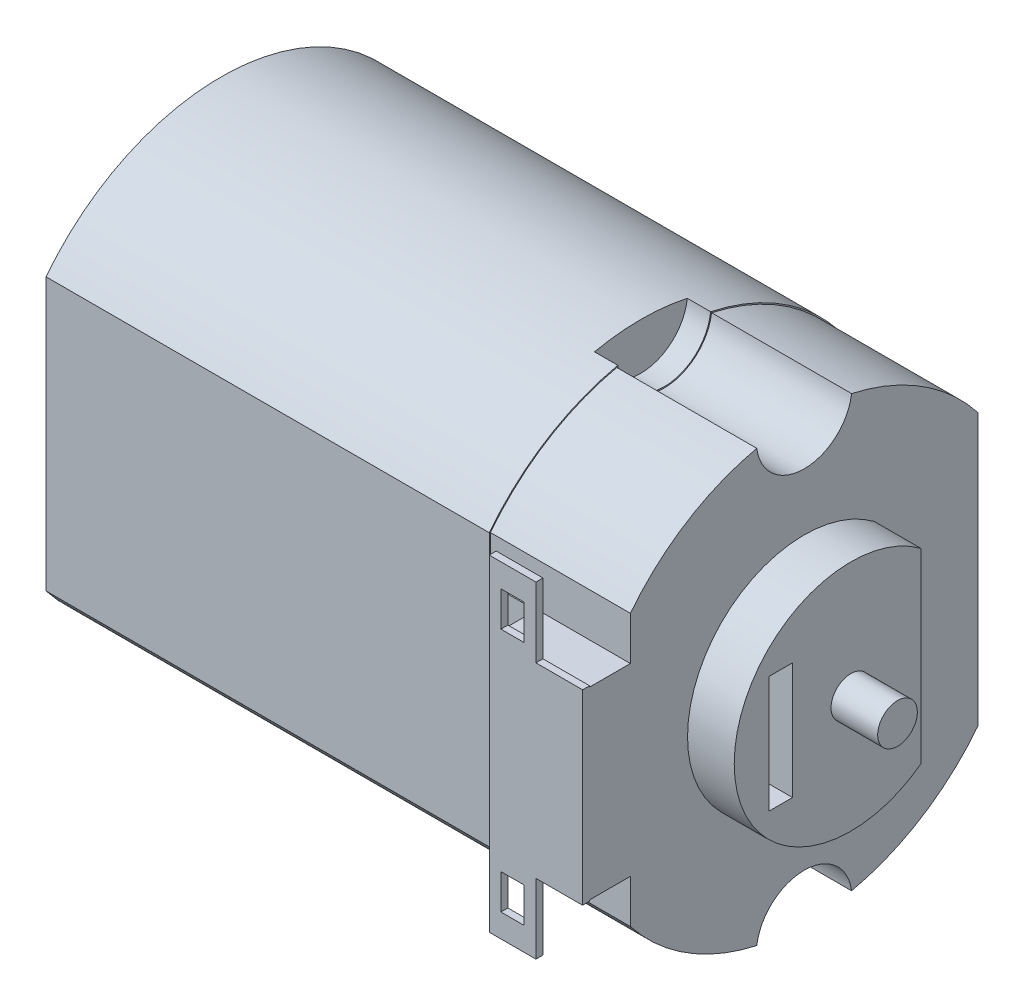
SolidWorks part; units mm, degrees
ref_plane "Front Plane" through (0, 0, 0) normal (0, 0, 1) x (1, 0, 0)
ref_plane "Top Plane" through (0, 0, 0) normal (0, 1, 0) x (1, 0, 0)
ref_plane "Right Plane" through (0, 0, 0) normal (1, 0, 0) x (0, 0, -1)
sketch "Sketch1" plane through (0, 0, 0) normal (1, 0, 0) x (0, 0, -1)
  line L2 (-7.5, 5.831) -> (-7.5, -5.831)
  line L4 (7.5, 5.831) -> (7.5, -5.831)
  line L5 (-7.5, 7.5) -> (7.5, -7.5) construction
  line L6 (-7.5, -7.5) -> (7.5, 7.5) construction
  arc A0 (-7.5, -5.831) -> (7.5, -5.831) centre (0, 0) ccw
  arc A1 (7.5, 5.831) -> (-7.5, 5.831) centre (0, 0) ccw
  dimension "D1" = 19
  dimension "D2" = 15
extrude "Boss-Extrude1" add sketch "Sketch1" along normal blind 25
sketch "Sketch2" plane through (25, 0, 0) normal (1, 0, 0) x (0, 0, -1)
  line L0 (0, -10.4614) -> (0, 9.9981) construction
  line L1 (-8.5237, 0) -> (12.0541, 0) construction
  circle A0 centre (0, 9.5) radius 2
  circle A1 centre (0, -9.5) radius 2
  dimension "D1" = 4
  dimension "D2" = 9.5
extrude "Cut-Extrude1" cut sketch "Sketch2" against normal blind 7
sketch "Sketch3" plane through (25, 0, 0) normal (1, 0, 0) x (0, 0, -1)
  line L0 (3, 4) -> (3, -4)
  line L1 (-8.9719, 0) -> (9.9494, 0) construction
  line L3 (-3.5, 2.5) -> (-2.5, 2.5)
  line L4 (-3.5, 2.5) -> (-3.5, -2.5)
  line L5 (-3.5, -2.5) -> (-2.5, -2.5)
  line L6 (-2.5, 2.5) -> (-2.5, -2.5)
  line L7 (-3.5, 2.5) -> (-2.5, -2.5) construction
  line L8 (-3.5, -2.5) -> (-2.5, 2.5) construction
  arc A0 (3, 4) -> (3, -4) centre (0, 0) ccw
  point P5 (-3, 0)
  dimension "D1" = 10
  dimension "D2" = 3
  dimension "D3" = 5
  dimension "D4" = 1
  dimension "D5" = 2.5
extrude "Boss-Extrude2" add sketch "Sketch3" along normal blind 2
sketch "Sketch4" plane through (27, 0, 0) normal (1, 0, 0) x (0, 0, -1)
  circle A0 centre (0, 0) radius 0.85
  dimension "D1" = 1.7
extrude "Boss-Extrude3" add sketch "Sketch4" along normal blind 2
sketch "Sketch5" plane through (0, 0, 7.5) normal (0, 0, 1) x (1, 0, 0)
  line L0 (25, 5.831) -> (25, -5.831) construction
  line L1 (25, 4) -> (21, 4)
  line L2 (25, 4) -> (25, -4)
  line L3 (25, -4) -> (21, -4)
  line L4 (21, 4) -> (21, -4)
  point P6 (23, 4)
  dimension "D1" = 2
  dimension "D2" = 8
  dimension "D3" = 4
extrude "Boss-Extrude4" add sketch "Sketch5" along normal blind 2
sketch "Sketch6" plane through (0, -4, 0) normal (0, -1, 0) x (1, 0, 0)
  line L1 (21, 9.5) -> (23, 9.5)
  line L2 (21, 9.5) -> (21, 9.2)
  line L3 (21, 9.2) -> (23, 9.2)
  line L4 (23, 9.5) -> (23, 9.2)
  dimension "D1" = 2
  dimension "D2" = 0.3
extrude "Boss-Extrude5" add sketch "Sketch6" along normal blind 3
mirror "Mirror1" about plane through (0, 0, 0) normal (0, 1, 0) of "Boss-Extrude5"
sketch "Sketch7" plane through (0, 0, 9.5) normal (0, 0, 1) x (1, 0, 0)
  line L0 (29.8009, 0) -> (19.4181, 0) construction
  line L1 (22, 7) -> (22, -7) construction
  line L2 (23, 7) -> (21, 7) construction
  line L3 (23, -7) -> (21, -7) construction
  line L4 (21.5, -6) -> (22.5, -6)
  line L5 (21.5, 6) -> (22.5, 6)
  line L6 (21.5, 6) -> (21.5, 4.5)
  line L7 (21.5, 4.5) -> (22.5, 4.5)
  line L8 (22.5, 6) -> (22.5, 4.5)
  line L9 (21.5, 6) -> (22.5, 4.5) construction
  line L10 (21.5, 4.5) -> (22.5, 6) construction
  line L11 (21.5, -6) -> (21.5, -4.5)
  line L12 (21.5, -4.5) -> (22.5, -4.5)
  line L13 (22.5, -6) -> (22.5, -4.5)
  point P9 (22, 5.25)
  dimension "D1" = 1
  dimension "D2" = 1.5
  dimension "D3" = 1
extrude "Cut-Extrude2" cut sketch "Sketch7" against normal blind 1
sketch "Sketch8" plane through (25, 0, 0) normal (1, 0, 0) x (0, 0, -1)
  line L0 (-7.45, 5.8138) -> (-7.45, 3.95)
  line L1 (-7.45, 3.95) -> (-9.2, 3.95)
  line L3 (-9.2, -3.95) -> (-7.45, -3.95)
  line L4 (-7.45, -3.95) -> (-7.45, -5.8138)
  line L5 (7.45, -5.8138) -> (7.45, 5.8138)
  line L6 (-7.5, 5.831) -> (-7.5, 4)
  line L7 (-7.5, 4) -> (-9.5, 4)
  line L8 (-9.5, 4) -> (-9.5, -4)
  line L9 (-9.5, -4) -> (-7.5, -4)
  line L10 (-7.5, -4) -> (-7.5, -5.831)
  line L11 (7.5, -5.831) -> (7.5, 5.831)
  line L12 (-7.5, 5.831) -> (-7.5, 4)
  line L13 (-7.5, 4) -> (-9.2, 4)
  line L15 (-9.2, -4) -> (-7.5, -4)
  line L16 (-7.5, -4) -> (-7.5, -5.831)
  line L17 (7.5, -5.831) -> (7.5, 5.831)
  line L18 (-9.2, 4) -> (-9.2, 3.95)
  line L19 (-9.2, -4) -> (-9.2, -3.95)
  line L20 (-9.45, -3.95) -> (-7.45, -3.95) construction
  line L21 (-9.5, -4) -> (-7.5, -4) construction
  line L22 (-9.45, 3.95) -> (-9.45, -3.95) construction
  line L23 (-9.5, 4) -> (-9.5, -4) construction
  line L24 (-7.5, 4) -> (-9.5, 4) construction
  line L25 (-7.45, 3.95) -> (-9.45, 3.95) construction
  arc A0 (-2.032, 9.2289) -> (-7.45, 5.8138) centre (0, 0) ccw
  arc A1 (-7.45, -5.8138) -> (-2.032, -9.2289) centre (0, 0) ccw
  arc A2 (2.032, -9.2289) -> (-2.032, -9.2289) centre (0, -9.5) ccw
  arc A3 (2.032, -9.2289) -> (7.45, -5.8138) centre (0, 0) ccw
  arc A4 (7.45, 5.8138) -> (2.032, 9.2289) centre (0, 0) ccw
  arc A5 (-2.032, 9.2289) -> (2.032, 9.2289) centre (0, 9.5) ccw
  arc A6 (-1.9889, 9.2895) -> (1.9889, 9.2895) centre (0, 9.5) ccw
  arc A7 (-1.9889, 9.2895) -> (-7.5, 5.831) centre (0, 0) ccw
  arc A8 (-7.5, -5.831) -> (-1.9889, -9.2895) centre (0, 0) ccw
  arc A9 (1.9889, -9.2895) -> (-1.9889, -9.2895) centre (0, -9.5) ccw
  arc A10 (1.9889, -9.2895) -> (7.5, -5.831) centre (0, 0) ccw
  arc A11 (7.5, 5.831) -> (1.9889, 9.2895) centre (0, 0) ccw
  arc A12 (-1.9889, 9.2895) -> (1.9889, 9.2895) centre (0, 9.5) ccw
  arc A13 (-1.9889, 9.2895) -> (-7.5, 5.831) centre (0, 0) ccw
  arc A14 (-7.5, -5.831) -> (-1.9889, -9.2895) centre (0, 0) ccw
  arc A15 (1.9889, -9.2895) -> (-1.9889, -9.2895) centre (0, -9.5) ccw
  arc A16 (1.9889, -9.2895) -> (7.5, -5.831) centre (0, 0) ccw
  arc A17 (7.5, 5.831) -> (1.9889, 9.2895) centre (0, 0) ccw
  dimension "D1" = 0
  dimension "D2" = 0.05
extrude "Cut-Extrude3" cut sketch "Sketch8" against normal blind 6
